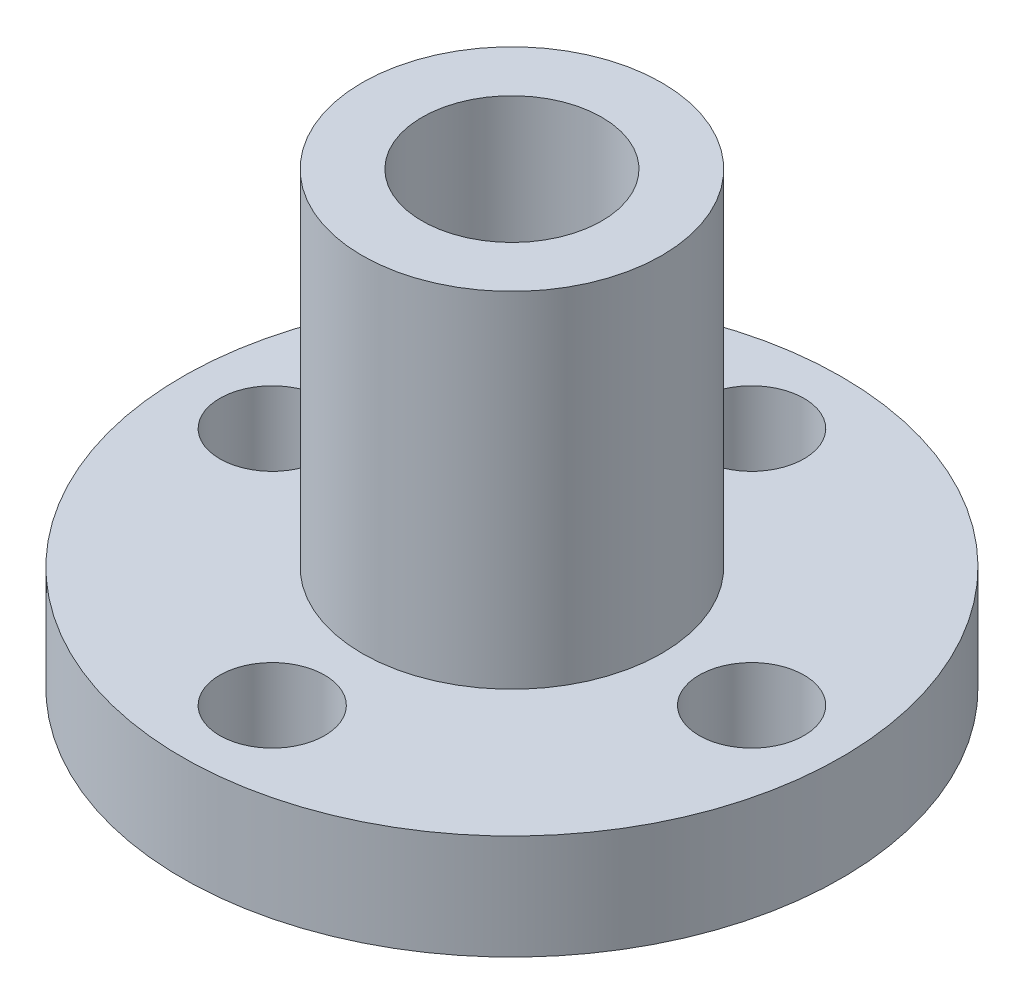
SolidWorks part; units mm, degrees
material "Leaded Commercial Bronze"
ref_plane "Front Plane" through (0, 0, 0) normal (0, 0, 1) x (1, 0, 0)
ref_plane "Top Plane" through (0, 0, 0) normal (0, 1, 0) x (1, 0, 0)
ref_plane "Right Plane" through (0, 0, 0) normal (1, 0, 0) x (0, 0, -1)
sketch "Sketch1" plane through (0, 0, 0) normal (0, 0, 1) x (1, 0, 0)
  line L0 (0, 0) -> (0, 15) construction
  line L1 (0, 15) -> (-5, 15) construction
  line L2 (-5, 15) -> (-5, 3.5)
  line L3 (-5, 3.5) -> (-11, 3.5)
  line L4 (-11, 3.5) -> (-11, 0)
  line L5 (-11, 0) -> (-3, 0)
  line L6 (-3, 0) -> (-3, 15)
  line L7 (-3, 15) -> (-5, 15)
  point P5 (-15.5003, 0)
  point P10 (0, 0)
  point P11 (-6, 3.7193)
  point P12 (-6, 22.9772)
  point P13 (0, 0)
  dimension "D1" = 6
  dimension "D2" = 22
  dimension "D3" = 11.5
  dimension "D4" = 3.5
  dimension "D5" = 10
revolve "Revolve1" add sketch "Sketch1" angle 360 about L0
sketch "Sketch2" plane through (0, 3.5, 0) normal (0, 1, 0) x (1, 0, 0)
  line L0 (0, 0) -> (0, 8) construction
  circle A0 centre (0, 8) radius 1.75
  circle A1 centre (8, 0) radius 1.75
  circle A2 centre (0, -8) radius 1.75
  circle A3 centre (-8, 0) radius 1.75
  point P4 (-8.7006, 1.6721)
  point P5 (0, 0)
  point P13 (0, 0)
  dimension "D1" = 3.5
  dimension "D2" = 8
  dimension "D3" = 4
extrude "Cut-Extrude1" cut sketch "Sketch2" against normal blind 10
